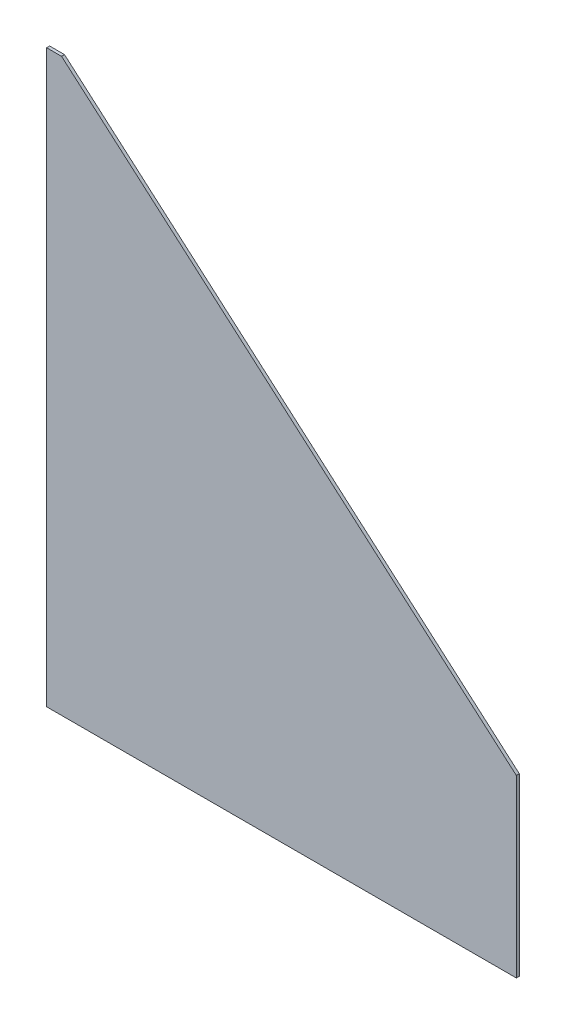
SolidWorks part; units mm, degrees
ref_plane "Front" through (0, 0, 0) normal (0, 0, 1) x (1, 0, 0)
ref_plane "Top" through (0, 0, 0) normal (0, 1, 0) x (1, 0, 0)
ref_plane "Right" through (0, 0, 0) normal (1, 0, 0) x (0, 0, -1)
sketch "Sketch1" plane through (0, 0, 0) normal (0, 0, 1) x (1, 0, 0)
  line L0 (0, 0) -> (-2006.6, 0)
  line L1 (0, 0) -> (0, 749.3)
  line L2 (-2006.6, 0) -> (-2006.6, 2438.4)
  line L3 (-2006.6, 2438.4) -> (-1943.1, 2438.4)
  line L4 (-1943.1, 2438.4) -> (0, 749.3)
  dimension "D1" = 2006.6
  dimension "D2" = 749.3
  dimension "D3" = 2438.4
  dimension "D4" = 63.5
extrude "Boss-Extrude1" add sketch "Sketch1" against normal blind 12.7
